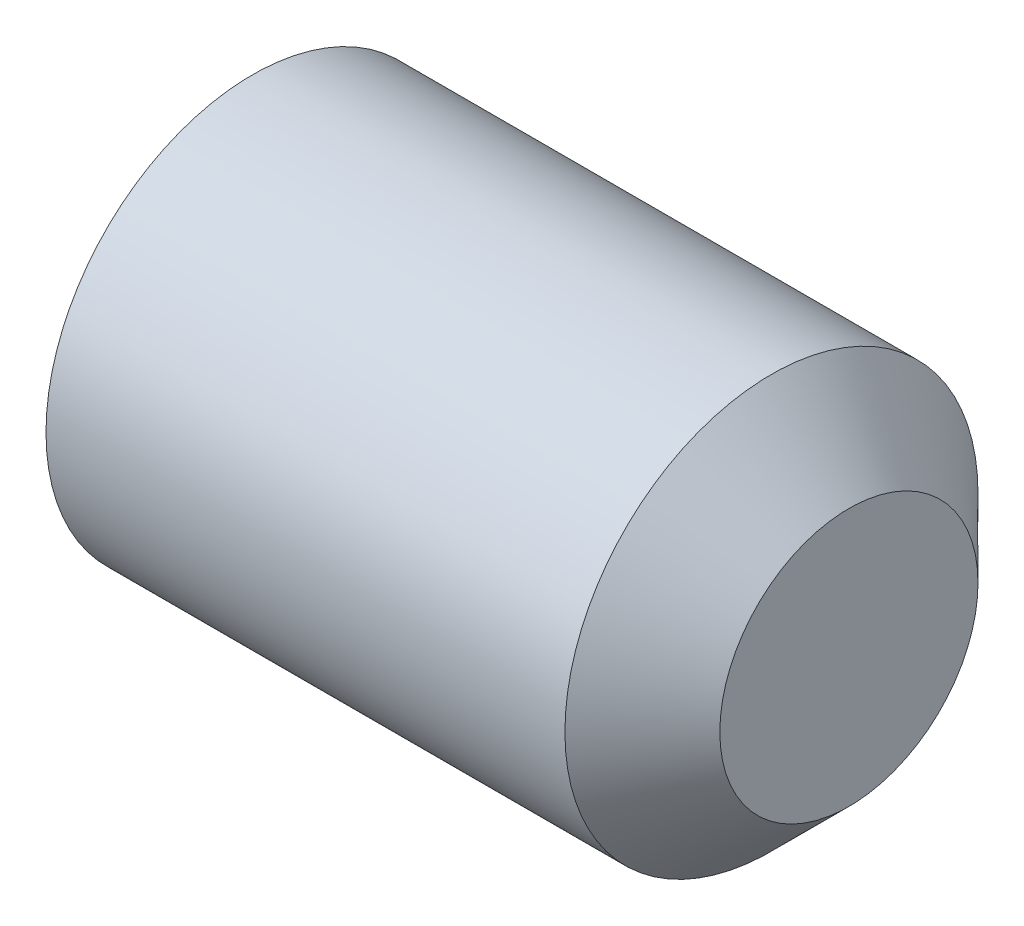
SolidWorks part; units mm, degrees
ref_plane "Plane1" through (0, 0, 0) normal (0, 0, 1) x (1, 0, 0)
ref_plane "Plane2" through (0, 0, 0) normal (0, 1, 0) x (1, 0, 0)
ref_plane "Plane3" through (0, 0, 0) normal (1, 0, 0) x (0, 0, -1)
sketch "BodySke" plane through (0, 0, 0) normal (0, 0, 1) x (1, 0, 0)
  line L0 (0, 0) -> (0, 1.61)
  line L1 (0, 1.61) -> (0.2252, 2)
  line L2 (0.2252, 2) -> (5.25, 2)
  line L3 (5.25, 2) -> (6, 1.25)
  line L4 (6, 0) -> (0, 0)
  line L5 (-12.7, 0) -> (88.9, 0) construction
  line L6 (6, 1.25) -> (6, 0)
  line L7 (6, 1.25) -> (6, 10.775) construction
  line L8 (0, -1.61) -> (0.2252, -2) construction
  line L9 (0.7, 15.875) -> (0.7, -3.175) construction
  line L10 (5.25, -2) -> (6, -1.25) construction
  dimension "Length" = 6
  dimension "Diameter" = 4
  dimension "Drive_ch_ang" = 60
  dimension "Minor_dia" = 3.22
  dimension "Cup_nose_ang" = 45
  dimension "Cup_dia" = 2.5
  dimension "Advance" = 0.7
revolve "BaseBody" add sketch "BodySke" angle 360 about L5
cosmetic thread "ThreadCosmetic" parameters "Thread_minor"=3.22
sketch "Sketch2" plane through (0, 0, 0) normal (-1, 0, 0) x (0, 0, 1)
  line L0 (0.5774, 1) -> (-0.5774, 1)
  line L1 (-0.5774, 1) -> (-1.1547, 0)
  line L2 (0.5774, 1) -> (1.1547, 0)
  line L3 (0.5774, -1) -> (1.1547, 0)
  line L4 (0.5774, -1) -> (-0.5774, -1)
  line L5 (-0.5774, -1) -> (-1.1547, 0)
  dimension "Hex_size" = 2
  dimension "D2" = 1
  dimension "D3" = 1
extrude "Hex" cut sketch "Sketch2" against normal blind 2.5
sketch "ThdSchSke" plane through (0, 0, 0) normal (0, 0, 1) x (1, 0, 0)
  line L0 (0.2252, -1.61) -> (-0.0479, -2)
  line L1 (0.2252, -1.61) -> (0.4982, -2)
  line L2 (0.4982, -2) -> (0.4982, -2.5)
  line L3 (-3.175, 0) -> (5.1513, 0) construction
  line L5 (0.4982, -2.5) -> (-0.0479, -2.5)
  line L6 (-0.0479, -2.5) -> (-0.0479, -2)
  line L8 (0.2252, 2) -> (0.2252, -2) construction
  dimension "Thread_minor" = 3.22
  dimension "Diameter" = 4
  dimension "SideAngle" = 55
  dimension "VeeAngle" = 70
  dimension "Overcut" = 5
revolve "ThreadSchematic" [suppressed] cut sketch "ThdSchSke" angle 360 about L3
pattern_linear "ThdSchPat" [suppressed]
equation "\"D2@Sketch2\" = \"Hex_size@Sketch2\" / 2"
equation "\"D3@Sketch2\" = \"Hex_size@Sketch2\" / 2"
equation "\"Thread_minor@ThreadCosmetic\" = \"Minor_dia@BodySke\""
equation "\"Thread_minor@ThdSchSke\" = \"Thread_minor@ThreadCosmetic\""
equation "\"Diameter@ThdSchSke\" = \"Diameter@BodySke\""
equation "\"Overcut@ThdSchSke\" = \"Diameter@BodySke\" * 1.25"
equation "\"Num_threads@ThdSchPat\" = int( (\"Length@BodySke\" - ( ( ( \"Diameter@BodySke\" - \"Minor_dia@BodySke\" ) * 0.5 ) / tan( \"Drive_ch_ang@BodySke\" * 0.017453292 ) ) - ( ( ( \"Diameter@BodySke\" - \"Cup_dia@BodySke\" ) * 0.5 ) * tan( \"Cup_nose_ang@BodySke\" * 0.017453292 ) ) ) / \"Advance@BodySke\" + 0.999 )  + 1"
equation "\"Advance@ThdSchPat\" = (\"Length@BodySke\" - ( ( ( \"Diameter@BodySke\" - \"Minor_dia@BodySke\" ) * 0.5 ) / tan( \"Drive_ch_ang@BodySke\" * 0.017453292 ) ) - ( ( ( \"Diameter@BodySke\" - \"Cup_dia@BodySke\" ) * 0.5 ) * tan( \"Cup_nose_ang@BodySke\" * 0.017453292 ) ) ) /  (\"Num_threads@ThdSchPat\" - 1) 'relax it"
equation "' \"Num_threads@ThdSchPat\" = \"Num_threads@ThdSchPat\" - sgn( \"Num_threads@ThdSchPat\" - 1) '---chamfered tips only---"
